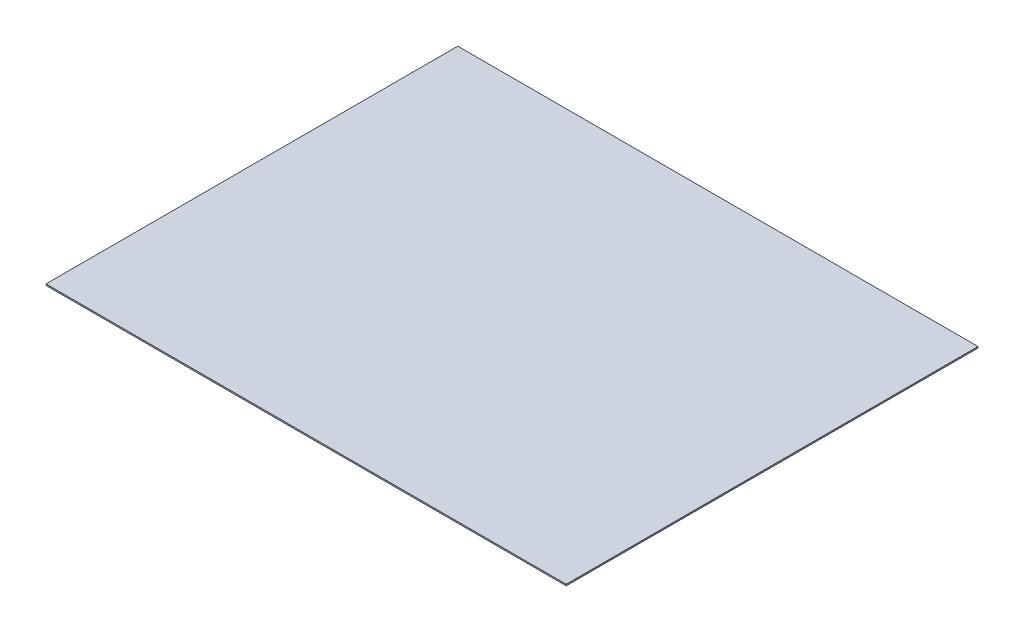
SolidWorks part; units mm, degrees
ref_plane "前视基准面" through (0, 0, 0) normal (0, 0, 1) x (1, 0, 0)
ref_plane "上视基准面" through (0, 0, 0) normal (0, 1, 0) x (1, 0, 0)
ref_plane "右视基准面" through (0, 0, 0) normal (1, 0, 0) x (0, 0, -1)
sketch "草图1" plane through (0, 0, 0) normal (0, 1, 0) x (1, 0, 0)
  line L0 (398.2858, 2295.1138) -> (691.9946, 2295.1138)
  line L1 (0, 0) -> (3790, 0)
  line L2 (0, 0) -> (0, 3000)
  line L3 (0, 3000) -> (3790, 3000)
  line L4 (3790, 0) -> (3790, 3000)
  line L5 (0, 2295.1138) -> (293.7087, 2295.1138)
  line L6 (0, 2295.1138) -> (0, 1816.7411)
  line L7 (0, 1816.7411) -> (293.7087, 1816.7411)
  line L8 (293.7087, 2295.1138) -> (293.7087, 1816.7411)
  line L9 (398.2858, 2295.1138) -> (398.2858, 1816.7411)
  line L10 (398.2858, 1816.7411) -> (691.9946, 1816.7411)
  line L11 (691.9946, 2295.1138) -> (691.9946, 1816.7411)
  line L12 (398.2858, 1695.1138) -> (691.9946, 1695.1138)
  line L13 (398.2858, 1695.1138) -> (398.2858, 1216.7411)
  line L14 (398.2858, 1216.7411) -> (691.9946, 1216.7411)
  line L15 (691.9946, 1695.1138) -> (691.9946, 1216.7411)
  line L16 (398.2858, 1095.1138) -> (691.9946, 1095.1138)
  line L17 (398.2858, 1095.1138) -> (398.2858, 616.7411)
  line L18 (398.2858, 616.7411) -> (691.9946, 616.7411)
  line L19 (691.9946, 1095.1138) -> (691.9946, 616.7411)
  line L20 (0, 1695.1138) -> (293.7087, 1695.1138)
  line L21 (0, 1695.1138) -> (0, 1216.7411)
  line L22 (0, 1216.7411) -> (293.7087, 1216.7411)
  line L23 (293.7087, 1695.1138) -> (293.7087, 1216.7411)
  line L24 (0, 1095.1138) -> (293.7087, 1095.1138)
  line L25 (0, 1095.1138) -> (0, 616.7411)
  line L26 (0, 616.7411) -> (293.7087, 616.7411)
  line L27 (293.7087, 1095.1138) -> (293.7087, 616.7411)
  line L28 (450, 400) -> (450, 0) construction
  line L29 (250, 0) -> (650, 0)
  line L30 (250, 0) -> (250, 400)
  line L31 (250, 400) -> (650, 400)
  line L32 (650, 0) -> (650, 400)
  line L34 (1948.6144, 1119.6561) -> (2348.6144, 1119.6561)
  line L35 (1948.6144, 1119.6561) -> (1948.6144, 1519.6561)
  line L36 (1948.6144, 1519.6561) -> (2348.6144, 1519.6561)
  line L37 (2348.6144, 1119.6561) -> (2348.6144, 1519.6561)
  line L39 (2268.227, 147.4524) -> (2668.227, 147.4524)
  line L40 (2268.227, 147.4524) -> (2268.227, 547.4524)
  line L41 (2268.227, 547.4524) -> (2668.227, 547.4524)
  line L42 (2668.227, 147.4524) -> (2668.227, 547.4524)
  point P41 (2725.5662, 612.1762)
  point P47 (2818.4451, 448.8762)
  point P48 (2268.227, 147.4524)
  dimension "D1" = 3790
  dimension "D2" = 3000
  dimension "D5" = 400
  dimension "D6" = 400
  dimension "D7" = 450
  dimension "D3" = 2
  dimension "D4" = 3
extrude "凸台-拉伸1" add sketch "草图1" along normal blind 10 contours L32 L1 L4 L3 L2 L5 L8 L7 L20 L23 L22 L24 L27 L26 L30 L31 L42 L39 L40 L41 L37 L34 L35 L36 L0 L11 L10 L9 L12 L15 L14 L13 L16 L19 L18 L17 | L8 L5 L2 L7 | L23 L20 L2 L22 | L11 L0 L9 L10 | L15 L12 L13 L14 | L27 L24 L2 L26 | L19 L16 L17 L18 | L31 L28 L29 L32 | L28 L31 L30 L1 | L34 L37 L36 L35 | L39 L42 L41 L40
